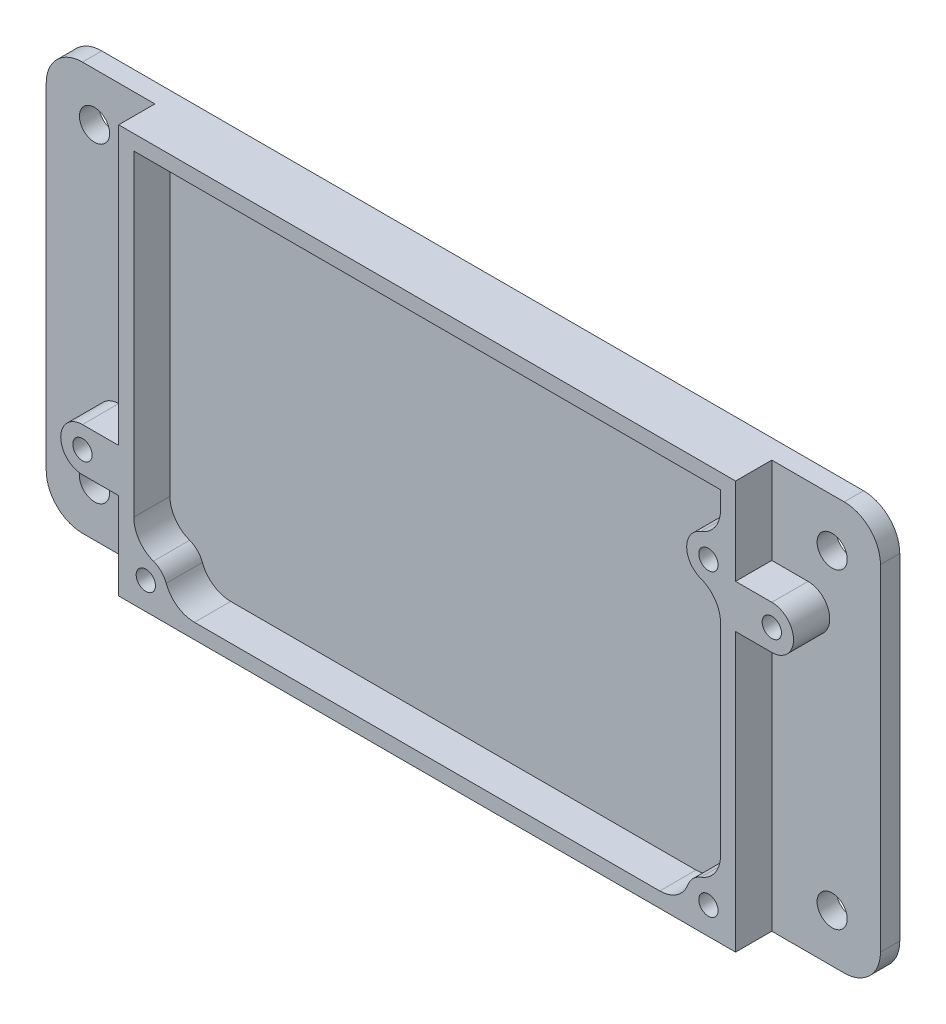
SolidWorks part; units mm, degrees
ref_plane "Front Plane" through (0, 0, 0) normal (0, 0, 1) x (1, 0, 0)
ref_plane "Top Plane" through (0, 0, 0) normal (0, 1, 0) x (1, 0, 0)
ref_plane "Right Plane" through (0, 0, 0) normal (1, 0, 0) x (0, 0, -1)
sketch "Sketch1" plane through (0, 0, 0) normal (0, 0, 1) x (1, 0, 0)
  line L0 (-6, 21.6) -> (0, 21.6)
  line L1 (0, 0) -> (102.2, 0)
  line L2 (0, 0) -> (0, 14.4)
  line L3 (0, 67.6) -> (102.2, 67.6)
  line L4 (102.2, 0) -> (102.2, 46)
  line L5 (2.5, 2.5) -> (99.7, 2.5)
  line L6 (2.5, 2.5) -> (2.5, 65.1)
  line L7 (2.5, 65.1) -> (99.7, 65.1)
  line L8 (99.7, 2.5) -> (99.7, 65.1)
  line L9 (-6, 14.4) -> (0, 14.4)
  line L10 (108.2, 53.2) -> (102.2, 53.2)
  line L11 (108.2, 46) -> (102.2, 46)
  line L12 (0, 21.6) -> (0, 67.6)
  line L13 (102.2, 53.2) -> (102.2, 67.6)
  circle A0 centre (4.5, 4.5) radius 1.6
  circle A1 centre (4.5, 4.5) radius 3.6
  circle A2 centre (97.7, 4.5) radius 1.6
  circle A3 centre (97.7, 4.5) radius 3.6
  circle A4 centre (97.7, 54.1) radius 1.6
  circle A5 centre (97.7, 54.1) radius 3.6
  circle A6 centre (-6, 18) radius 1.6
  arc A7 (-6, 21.6) -> (-6, 14.4) centre (-6, 18) ccw
  circle A8 centre (108.2, 49.6) radius 1.6
  arc A9 (108.2, 46) -> (108.2, 53.2) centre (108.2, 49.6) ccw
  dimension "D7" = 3.2
  dimension "D11" = 3.2
  dimension "D16" = 3.2
  dimension "D18" = 3.2
  dimension "D22" = 3.2
  dimension "D1" = 102.2
  dimension "D2" = 67.6
  dimension "D3" = 2.5
  dimension "D4" = 2.5
  dimension "D5" = 2.5
  dimension "D6" = 2.5
  dimension "D8" = 2
  dimension "D9" = 4.5
  dimension "D10" = 4.5
  dimension "D12" = 2
  dimension "D13" = 4.5
  dimension "D14" = 4.5
  dimension "D15" = 2
  dimension "D17" = 49.6
  dimension "D19" = 2
  dimension "D20" = 6
  dimension "D21" = 18
  dimension "D23" = 2
  dimension "D24" = 6
  dimension "D25" = 18
extrude "Boss-Extrude1" add sketch "Sketch1" along normal blind 6 contours L1 L4 L3 L2 A5 L8 A3 L5 A1 L6 L7 | L8 A5 A4 | L8 A3 L5 A2 | L5 A1 L6 A0 | L6 A1 L5 | L5 A3 L8 | L8 A5 | A6 | A9
sketch "Sketch2" plane through (0, 0, 0) normal (0, 0, -1) x (-1, 0, 0)
  line L0 (0, 67.6) -> (-102.2, 67.6) construction
  line L1 (-120.2, 0) -> (18, 0)
  line L2 (-120.2, 0) -> (-120.2, 67.6)
  line L3 (-120.2, 67.6) -> (18, 67.6)
  line L4 (18, 0) -> (18, 67.6)
  line L5 (0, 0) -> (-102.2, 0) construction
  line L6 (0, 21.6) -> (0, 67.6) construction
  line L7 (-51.1, 67.6) -> (-51.1, 0) construction
  line L8 (-102.2, 53.2) -> (-102.2, 67.6) construction
  circle A0 centre (-112.2, 59.6) radius 2.5
  circle A1 centre (-112.2, 8) radius 2.5
  circle A2 centre (10, 8) radius 2.5
  circle A3 centre (10, 59.6) radius 2.5
  dimension "D3" = 5
  dimension "D4" = 5
  dimension "D6" = 8
  dimension "D7" = 8
  dimension "D5" = 8
  dimension "D2" = 18
  dimension "D1" = 18
extrude "Boss-Extrude2" add sketch "Sketch2" along normal blind 3.2
fillet "Fillet1" radius 6 4 edges at (120.2, 67.6, -1.6) (120.2, 0, -1.6) (-18, 67.6, -1.6) (-18, 0, -1.6)
fillet "Fillet2" radius 5 2 edges at (99.7, 51.1067, 3) (99.7, 57.0933, 3)
fillet "Fillet3" radius 5 4 edges at (7.4933, 2.5, 3) (2.5, 7.4933, 3) (94.7067, 2.5, 3) (99.7, 7.4933, 3)
equation "\"M3HoleInner\"= 3.2mm"
equation "\"M3HoleThickness\"= 2mm"
equation "\"M3DistY\"= 49.6mm"
equation "\"M3DistX\"= 93mm"
equation "\"BoardX\"= 102.2mm"
equation "\"BoardY\"= 67.6mm"
equation "\"D1@Sketch1\"=\"BoardX\""
equation "\"D2@Sketch1\"=\"BoardY\""
equation "\"BoardThickness\"= 2.5mm"
equation "\"D3@Sketch1\"=\"BoardThickness\""
equation "\"D4@Sketch1\"=\"BoardThickness\""
equation "\"D5@Sketch1\"=\"BoardThickness\""
equation "\"D6@Sketch1\"=\"BoardThickness\""
equation "\"D7@Sketch1\"=\"M3HoleInner\""
equation "\"D8@Sketch1\"=\"M3HoleThickness\""
equation "\"D11@Sketch1\"=\"M3HoleInner\""
equation "\"D12@Sketch1\"=\"M3HoleThickness\""
equation "\"D15@Sketch1\"=\"M3HoleThickness\""
equation "\"D16@Sketch1\"=\"M3HoleInner\""
equation "\"D17@Sketch1\"=\"M3DistY\""
equation "\"MountFlangWidth\"= 18mm"
equation "\"MountFlangHoles\"= 5.0mm"
equation "\"D3@Sketch2\"=\"MountFlangHoles\""
equation "\"D4@Sketch2\"=\"MountFlangHoles\""
equation "\"D7@Sketch2\"=8"
equation "\"D18@Sketch1\"=\"M3HoleInner\""
equation "\"D19@Sketch1\"=\"M3HoleThickness\""
equation "\"D22@Sketch1\"=\"M3HoleInner\""
equation "\"D23@Sketch1\"=\"M3HoleThickness\""
equation "\"D2@Sketch2\"=\"MountFlangWidth\""
equation "\"D1@Sketch2\"=\"MountFlangWidth\""
